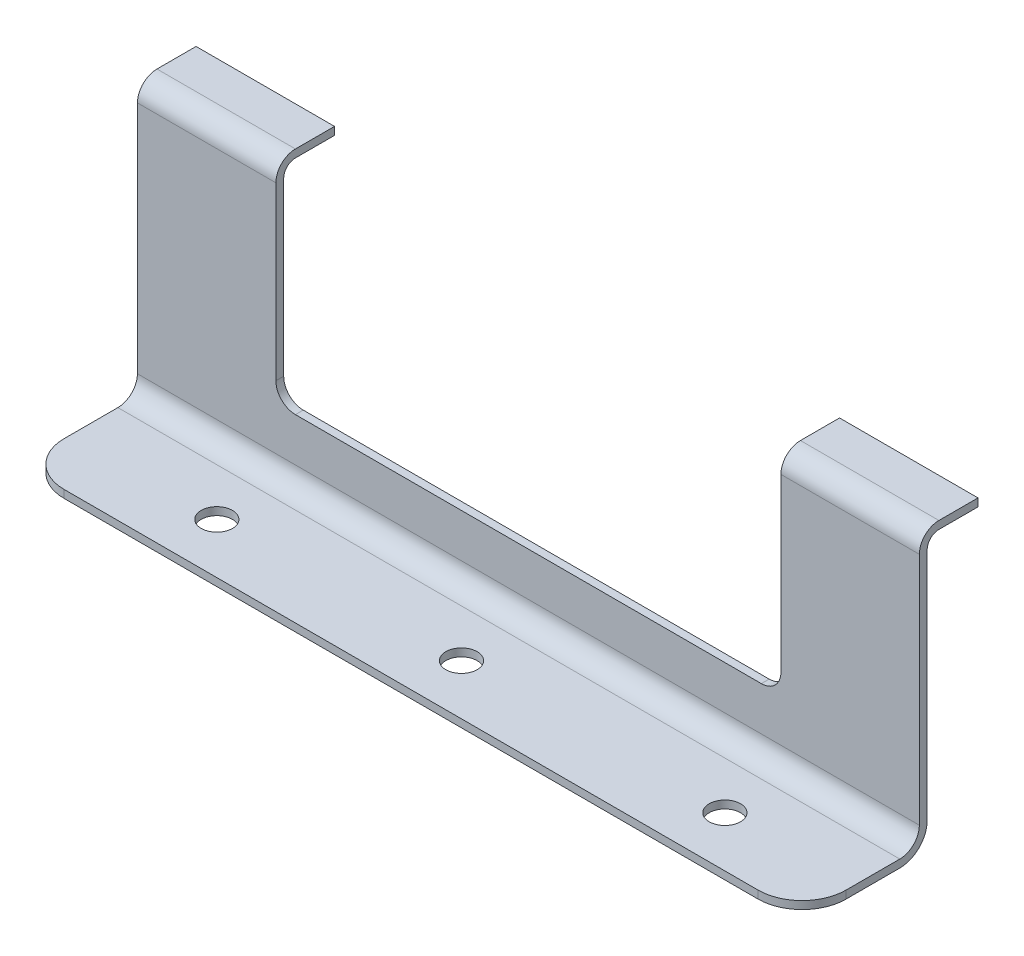
SolidWorks part; units mm, degrees
ref_plane "Front Plane" through (0, 0, 0) normal (0, 0, 1) x (1, 0, 0)
ref_plane "Top Plane" through (0, 0, 0) normal (0, 1, 0) x (1, 0, 0)
ref_plane "Right Plane" through (0, 0, 0) normal (1, 0, 0) x (0, 0, -1)
sketch "Sketch1" plane through (0, 0, 0) normal (1, 0, 0) x (0, 0, -1)
  line L0 (4.4034, 32.2727) -> (-5.5966, 32.2727)
  line L1 (-10.5966, 27.2727) -> (-10.5966, -32.7273)
  line L2 (-15.5966, -37.7273) -> (-40.5966, -37.7273)
  line L3 (4.4034, 30.2727) -> (-5.5966, 30.2727)
  line L4 (-8.5966, 27.2727) -> (-8.5966, -32.7273)
  line L5 (-15.5966, -39.7273) -> (-40.5966, -39.7273)
  line L6 (4.4034, 30.2727) -> (4.4034, 32.2727)
  line L7 (-40.5966, -39.7273) -> (-40.5966, -37.7273)
  arc A0 (-10.5966, -32.7273) -> (-15.5966, -37.7273) centre (-15.5966, -32.7273) cw
  arc A1 (-5.5966, 32.2727) -> (-10.5966, 27.2727) centre (-5.5966, 27.2727) ccw
  arc A2 (-5.5966, 30.2727) -> (-8.5966, 27.2727) centre (-5.5966, 27.2727) ccw
  arc A3 (-8.5966, -32.7273) -> (-15.5966, -39.7273) centre (-15.5966, -32.7273) cw
  point P6 (-10.5966, -37.7273)
  point P9 (-10.5966, 32.2727)
  dimension "D4" = 5
  dimension "D1" = 70
  dimension "D2" = 15
  dimension "D3" = 30
  dimension "D5" = 2
extrude "Boss-Extrude1" add sketch "Sketch1" along normal mid plane 200
sketch "Sketch2" plane through (0, 32.2727, 0) normal (0, 1, 0) x (1, 0, 0)
  line L7 (-100, -15.5966) -> (-100, -40.5966) construction
  line L8 (100, -40.5966) -> (-100, -40.5966) construction
  line L9 (-88.753, -40.5966) -> (-100, -40.5966)
  line L10 (-100, -40.5966) -> (-100, -29.3497)
  line L11 (100, -40.5966) -> (100, -29.3497)
  line L12 (88.753, -40.5966) -> (100, -40.5966)
  arc A2 (-100, -29.3497) -> (-88.753, -40.5966) centre (-88.753, -29.3497) ccw
  arc A3 (100, -29.3497) -> (88.753, -40.5966) centre (88.753, -29.3497) cw
  circle A4 centre (0, -27.7074) radius 4
  circle A5 centre (-62.5769, -27.7074) radius 4
  circle A6 centre (67.372, -27.7074) radius 4
  point P34 (-62.5769, -27.2803)
  dimension "D1" = 8
extrude "Cut-Extrude1" cut sketch "Sketch2" against normal blind 200
sketch "Sketch3" plane through (0, 0, 10.5966) normal (0, 0, 1) x (1, 0, 0)
  line L1 (-64.5845, 178.4544) -> (64.5845, 178.4544)
  line L2 (-64.5845, 178.4544) -> (-64.5845, -16.5731)
  line L3 (-59.5845, -21.5731) -> (59.5845, -21.5731)
  line L4 (64.5845, 178.4544) -> (64.5845, -16.5731)
  line L5 (-64.5845, 178.4544) -> (64.5845, -21.5731) construction
  line L6 (-64.5845, -21.5731) -> (64.5845, 178.4544) construction
  arc A0 (-64.5845, -16.5731) -> (-59.5845, -21.5731) centre (-59.5845, -16.5731) ccw
  arc A1 (59.5845, -21.5731) -> (64.5845, -16.5731) centre (59.5845, -16.5731) ccw
  point P0 (0, 78.4406)
  dimension "D1" = 5
extrude "Cut-Extrude2" cut sketch "Sketch3" against normal blind 200
scale "Scale1" bodies to scale 103 scale about origin uniform scaling yes scale factor 2
